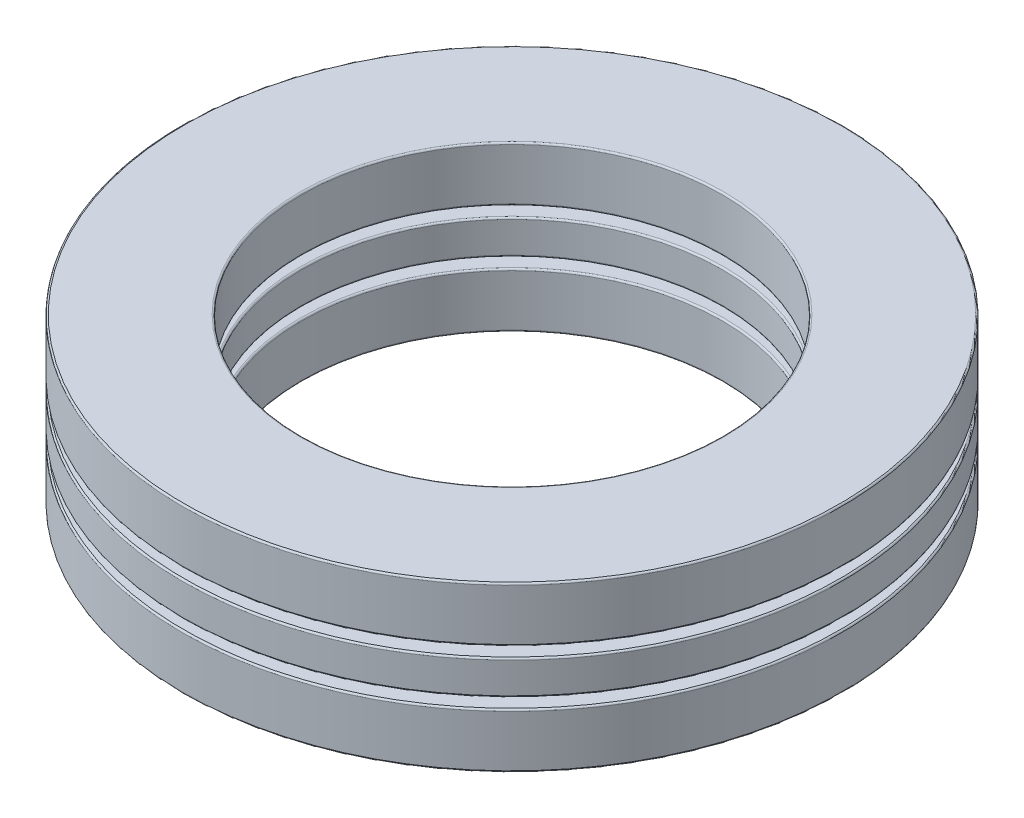
SolidWorks part; units mm, degrees
ref_plane "Front Plane" through (0, 0, 0) normal (0, 0, 1) x (1, 0, 0)
ref_plane "Top Plane" through (0, 0, 0) normal (0, 1, 0) x (1, 0, 0)
ref_plane "Right Plane" through (0, 0, 0) normal (1, 0, 0) x (0, 0, -1)
sketch "Sketch1" plane through (0, 0, 0) normal (1, 0, 0) x (0, 0, -1)
  line L0 (-17.4625, 0) -> (17.4625, 0) construction
  line L1 (0, -4.3434) -> (0, 4.3434) construction
  line L2 (-17.4625, 0.9049) -> (-11.1506, 0.9049)
  line L3 (-17.4625, 0.9049) -> (-17.4625, -0.9049)
  line L4 (-17.4625, -0.9049) -> (-11.1506, -0.9049)
  line L5 (-11.1506, 0.9049) -> (-11.1506, -0.9049)
  line L6 (-14.3066, 1.4478) -> (-14.3066, -1.4478) construction
  circle A0 centre (-14.3066, 0) radius 1.4478 construction
  point P13 (-14.3066, 0.9049)
  dimension "OD" = 34.925
  dimension "Shaft Dia" = 22.3012
  dimension "Th" = 8.6868
  dimension "D1" = 2.8956
  dimension "D2" = 1.8098
revolve "Revolve1" add sketch "Sketch1" angle 360 about L1
sketch "Sketch3" plane through (0, 0, 0) normal (1, 0, 0) x (0, 0, -1)
  line L0 (-14.3066, 1.4478) -> (-14.3066, -1.4478)
  arc A0 (-14.3066, 1.4478) -> (-14.3066, -1.4478) centre (-14.3066, 0) ccw
  circle A1 centre (-14.3066, 0) radius 1.4478 construction
revolve "Cut-Revolve1" cut sketch "Sketch3" angle 360 about L0
sketch "Sketch2" plane through (0, 0, 0) normal (1, 0, 0) x (0, 0, -1)
  line L0 (-14.3066, 1.4478) -> (-14.3066, -1.4478)
  arc A0 (-14.3066, 1.4478) -> (-14.3066, -1.4478) centre (-14.3066, 0) ccw
  circle A2 centre (-14.3066, 0) radius 1.4478 construction
revolve "Revolve2" add sketch "Sketch2" angle 360 about L0
ref_axis "Axis1" through (0, 4.3434, 0) along (0, -1, 0)
pattern_circular "CirPattern1" count 7 every 51.429 about axis through (0, 4.3434, 0) along (0, -1, 0) of bodies 187
pattern_circular "CirPattern2" count 7 every 51.429 about axis through (0, 0, 0) along (0, 1, 0) of "Cut-Revolve1"
sketch "Sketch4" plane through (0, 0, 0) normal (1, 0, 0) x (0, 0, -1)
  line L0 (-17.4625, 0.9049) -> (-17.4625, -0.9049) construction
  line L1 (-17.4625, 1.4478) -> (-11.1506, 1.4478)
  line L2 (-17.4625, 1.4478) -> (-17.4625, 4.3434)
  line L3 (-17.4625, 4.3434) -> (-11.1506, 4.3434)
  line L4 (-11.1506, 1.4478) -> (-11.1506, 4.3434)
  line L5 (-17.4625, -4.3434) -> (-11.1506, -4.3434)
  line L6 (-17.4625, -4.3434) -> (-17.4625, -1.4478)
  line L7 (-17.4625, -1.4478) -> (-11.1506, -1.4478)
  line L8 (-11.1506, -4.3434) -> (-11.1506, -1.4478)
  line L9 (-14.3066, 1.4478) -> (-14.3066, -1.4478) construction
  line L10 (-11.1506, 0.9049) -> (-11.1506, -0.9049) construction
  line L11 (0, 0) -> (-17.4625, 0) construction
  line L12 (-17.4625, 0) -> (17.4625, 0) construction
  dimension "Ht" = 8.6868
revolve "Revolve3" add sketch "Sketch4" angle 360 about L1
fillet "Fillet1" radius 0.0869 4 edges at (0, 1.4478, -11.1506) (0, 4.3434, -11.1506) (0, 1.4478, -17.4625) (0, 4.3434, -17.4625)
fillet "Fillet2" radius 0.0869 4 edges at (0, -0.9049, -11.1506) (0, 0.9049, -11.1506) (0, -0.9049, -17.4625) (0, 0.9049, -17.4625)
fillet "Fillet3" radius 0.0869 4 edges at (0, -4.3434, -11.1506) (0, -1.4478, -11.1506) (0, -4.3434, -17.4625) (0, -1.4478, -17.4625)
equation "\"D1@Sketch1\" = \"Th@Sketch1\"/3"
equation "\"D2@Sketch1\" = \"D1@Sketch1\"*.625"
equation "\"Balls@CirPattern1\" = \"OD@Sketch1\"*5"
equation "\"Angle@CirPattern1\" = 360/\"Balls@CirPattern1\""
equation "\"D1@CirPattern2\" = \"Balls@CirPattern1\""
equation "\"D2@CirPattern2\" = \"Angle@CirPattern1\""
equation "\"D1@Fillet1\" = \"Th@Sketch1\"*.01"
equation "\"D1@Fillet2\" = \"D1@Fillet1\""
equation "\"D1@Fillet3\" = \"D1@Fillet1\""
